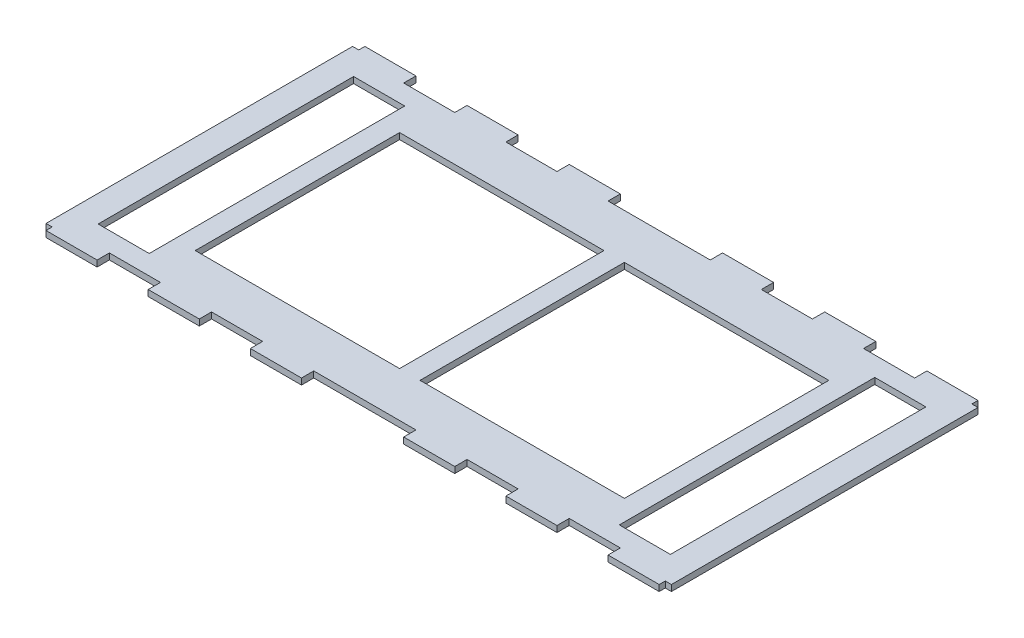
SolidWorks part; units mm, degrees
ref_plane "前视基准面" through (0, 0, 0) normal (0, 0, 1) x (1, 0, 0)
ref_plane "上视基准面" through (0, 0, 0) normal (0, 1, 0) x (1, 0, 0)
ref_plane "右视基准面" through (0, 0, 0) normal (1, 0, 0) x (0, 0, -1)
sketch "草图1" plane through (0, 0, 0) normal (0, 1, 0) x (1, 0, 0)
  line L0 (330, 300) -> (330, 150)
  line L1 (30, 300) -> (24, 300)
  line L2 (24, 300) -> (24, 0)
  line L3 (630, 300) -> (630, 306)
  line L4 (630, 306) -> (580, 306)
  line L5 (330, 150) -> (340, 150)
  line L6 (340, 150) -> (340, 250)
  line L7 (340, 250) -> (540, 250)
  line L8 (540, 250) -> (540, 50)
  line L9 (540, 50) -> (340, 50)
  line L10 (340, 50) -> (340, 150)
  line L11 (540, 150) -> (560, 150)
  line L12 (560, 150) -> (560, 275)
  line L13 (560, 275) -> (610, 275)
  line L14 (610, 275) -> (610, 25)
  line L15 (610, 25) -> (560, 25)
  line L16 (560, 25) -> (560, 150)
  line L19 (580, 306) -> (580, 294)
  line L20 (580, 294) -> (530, 294)
  line L21 (530, 294) -> (530, 306)
  line L22 (530, 306) -> (480, 306)
  line L23 (480, 306) -> (480, 294)
  line L24 (480, 294) -> (430, 294)
  line L25 (430, 294) -> (430, 306)
  line L26 (430, 306) -> (380, 306)
  line L27 (380, 306) -> (380, 294)
  line L28 (380, 294) -> (280, 294)
  line L29 (380, 6) -> (280, 6)
  line L30 (380, -6) -> (380, 6)
  line L31 (430, -6) -> (380, -6)
  line L32 (430, 6) -> (430, -6)
  line L33 (480, 6) -> (430, 6)
  line L34 (480, -6) -> (480, 6)
  line L35 (530, -6) -> (480, -6)
  line L36 (530, 6) -> (530, -6)
  line L37 (580, 6) -> (530, 6)
  line L38 (580, -6) -> (580, 6)
  line L39 (630, -6) -> (580, -6)
  line L40 (630, 0) -> (630, -6)
  line L41 (30, 0) -> (30, -6)
  line L42 (30, -6) -> (80, -6)
  line L43 (80, -6) -> (80, 6)
  line L44 (80, 6) -> (130, 6)
  line L45 (130, 6) -> (130, -6)
  line L46 (130, -6) -> (180, -6)
  line L47 (180, -6) -> (180, 6)
  line L48 (180, 6) -> (230, 6)
  line L49 (230, 6) -> (230, -6)
  line L50 (230, -6) -> (280, -6)
  line L51 (280, -6) -> (280, 6)
  line L52 (280, 306) -> (280, 294)
  line L53 (230, 306) -> (280, 306)
  line L54 (230, 294) -> (230, 306)
  line L55 (180, 294) -> (230, 294)
  line L56 (180, 306) -> (180, 294)
  line L57 (130, 306) -> (180, 306)
  line L58 (130, 294) -> (130, 306)
  line L59 (80, 294) -> (130, 294)
  line L60 (80, 306) -> (80, 294)
  line L62 (100, 25) -> (100, 150)
  line L63 (50, 25) -> (100, 25)
  line L64 (50, 275) -> (50, 25)
  line L65 (100, 275) -> (50, 275)
  line L66 (100, 150) -> (100, 275)
  line L67 (120, 150) -> (100, 150)
  line L68 (320, 50) -> (320, 150)
  line L69 (120, 50) -> (320, 50)
  line L70 (120, 250) -> (120, 50)
  line L71 (320, 250) -> (120, 250)
  line L72 (320, 150) -> (320, 250)
  line L73 (30, 306) -> (80, 306)
  line L74 (30, 300) -> (30, 306)
  line L75 (24, 0) -> (30, 0)
  line L76 (630, 300) -> (636, 300)
  line L77 (636, 300) -> (636, 0)
  line L78 (636, 0) -> (630, 0)
  point P53 (330, 6)
  point P54 (330, 294)
extrude "凸台-拉伸1" add sketch "草图1" along normal blind 6
